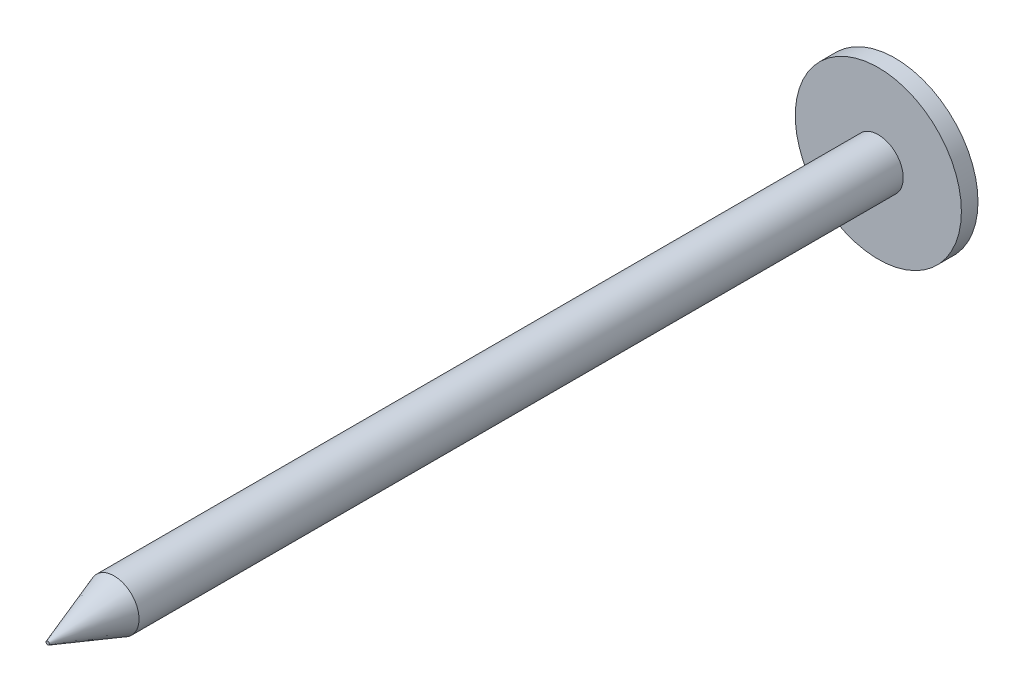
SolidWorks part; units mm, degrees
ref_plane "Front Plane" through (0, 0, 0) normal (0, 0, 1) x (1, 0, 0)
ref_plane "Top Plane" through (0, 0, 0) normal (0, 1, 0) x (1, 0, 0)
ref_plane "Right Plane" through (0, 0, 0) normal (1, 0, 0) x (0, 0, -1)
sketch "Sketch1" plane through (0, 0, 0) normal (0, 0, 1) x (1, 0, 0)
  circle A0 centre (0, 0) radius 2.5
  dimension "D1" = 5
extrude "Extrude1" add sketch "Sketch1" along normal blind 0.5
sketch "Sketch2" plane through (0, 0, 0.5) normal (0, 0, 1) x (1, 0, 0)
  circle A0 centre (0, 0) radius 0.75
  dimension "D1" = 1.5
extrude "Extrude2" add sketch "Sketch2" along normal blind 25
chamfer "Chamfer1" distance 2 distance2 0.7 1 edges at (0.75, 0, 25.5)
